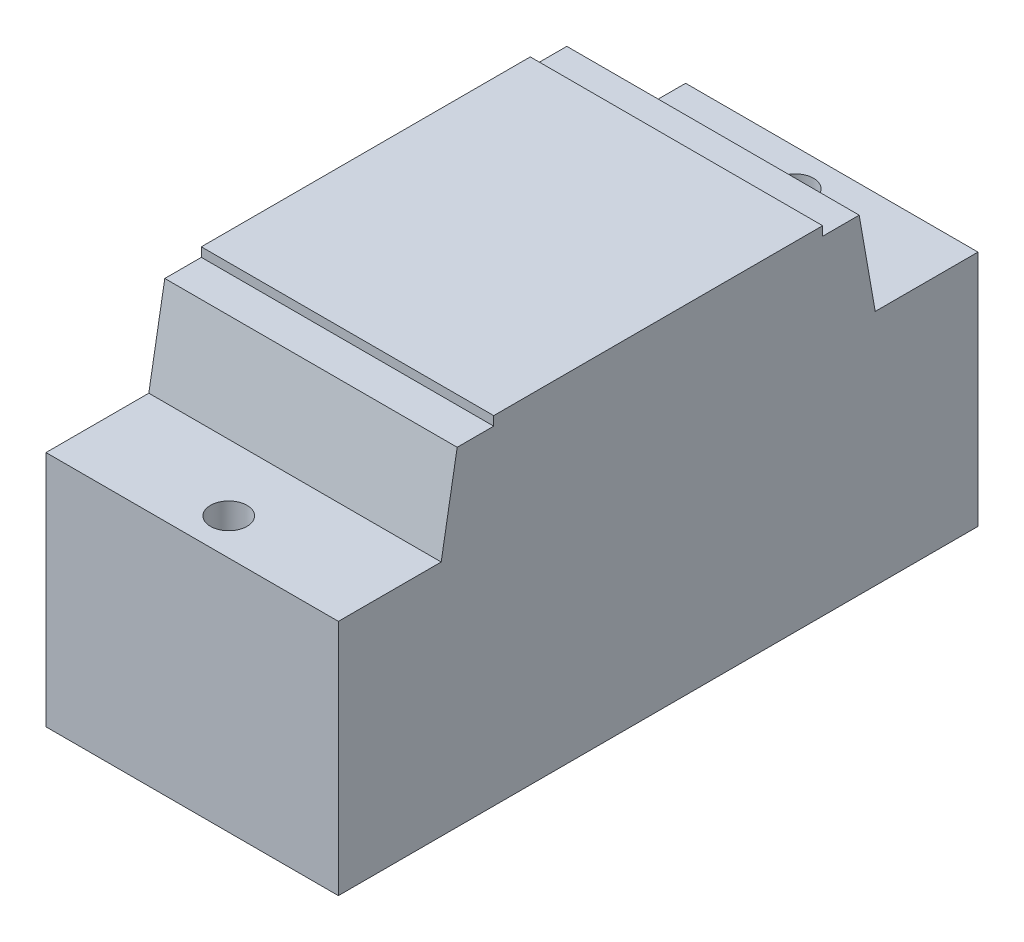
SolidWorks part; units mm, degrees
ref_plane "正面" through (0, 0, 0) normal (0, 0, 1) x (1, 0, 0)
ref_plane "平面" through (0, 0, 0) normal (0, 1, 0) x (1, 0, 0)
ref_plane "右側面" through (0, 0, 0) normal (1, 0, 0) x (0, 0, -1)
sketch "ｽｹｯﾁ1" plane through (0, 0, 0) normal (0, 1, 0) x (1, 0, 0)
  line L1 (-16, 35) -> (16, 35)
  line L2 (-16, 35) -> (-16, -35)
  line L3 (-16, -35) -> (16, -35)
  line L4 (16, 35) -> (16, -35)
  line L5 (-16, 35) -> (16, -35) construction
  line L6 (-16, -35) -> (16, 35) construction
  point P0 (0, 0)
  dimension "D1" = 32
  dimension "D2" = 70
extrude "ﾎﾞｽ - 押し出し1" add sketch "ｽｹｯﾁ1" along normal blind 26
sketch "ｽｹｯﾁ2" plane through (16, 0, 0) normal (1, 0, 0) x (0, 0, -1)
  line L0 (0, 0) -> (0, 31) construction
  line L1 (-35, 26) -> (35, 26) construction
  line L2 (-22, 36) -> (22, 36)
  line L3 (-22, 36) -> (-22, 26)
  line L4 (-22, 26) -> (22, 26)
  line L5 (22, 36) -> (22, 26)
  line L6 (-22, 36) -> (22, 26) construction
  line L7 (-22, 26) -> (22, 36) construction
  line L8 (-22, 36) -> (-23.75, 26)
  line L9 (22, 36) -> (23.75, 26)
  line L10 (0, 36) -> (0, 36.5) construction
  line L12 (-18, 37) -> (18, 37)
  line L13 (-35, 0) -> (35, 0)
  line L14 (35, 0) -> (35, 26)
  line L15 (35, 26) -> (-35, 26)
  line L16 (-35, 26) -> (-35, 0)
  line L17 (-35, 0) -> (35, 0)
  line L18 (35, 0) -> (35, 26)
  line L19 (35, 26) -> (-35, 26)
  line L20 (-35, 26) -> (-35, 0)
  line L21 (-18, 37) -> (-18, 36)
  line L22 (-18, 36) -> (18, 36)
  line L23 (18, 37) -> (18, 36)
  line L24 (-18, 37) -> (18, 36) construction
  line L25 (-18, 36) -> (18, 37) construction
  line M11 (35, 26) -> (-35, 26)
  dimension "D1" = 10
  dimension "D2" = 44
  dimension "D4" = 47.5
  dimension "D5" = 36
  dimension "D6" = 1
  dimension "D3" = 0
extrude "ﾎﾞｽ - 押し出し2" add sketch "ｽｹｯﾁ2" against normal blind 32 contours L5 L2 L3 M11 | L23 L12 L21 L2 | L3 L8 M11 | L9 L5 M11
sketch "ｽｹｯﾁ3" plane through (0, 0, 0) normal (0, -1, 0) x (1, 0, 0)
  line L0 (0, 0) -> (16, 0) construction
  line L1 (16, 35) -> (16, -35) construction
  line L2 (0, 0) -> (0, 31) construction
  circle A0 centre (0, 31) radius 2
  circle A1 centre (0, -31) radius 2
  dimension "D1" = 4
  dimension "D2" = 62
extrude "ｶｯﾄ - 押し出し1" cut sketch "ｽｹｯﾁ3" against normal through all
